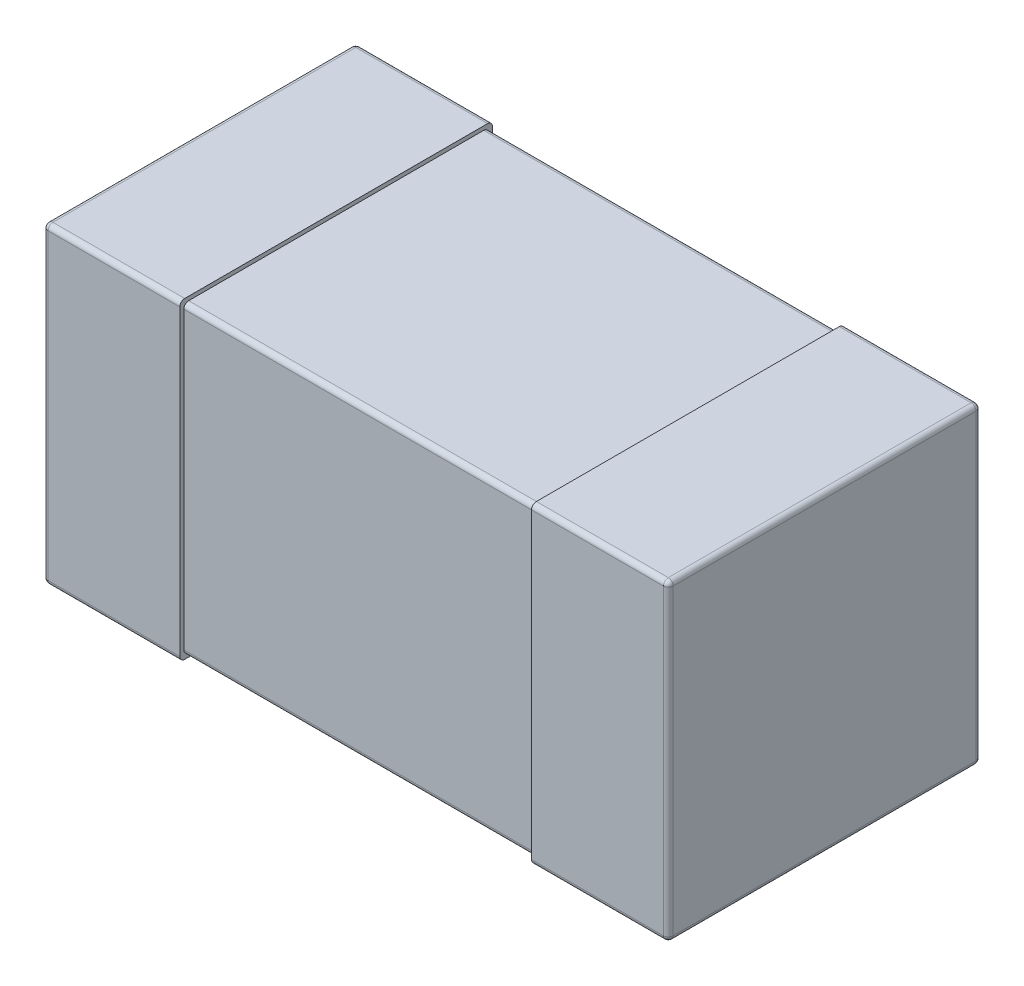
SolidWorks part; units mm, degrees
ref_plane "Спереди" through (0, 0, 0) normal (0, 0, 1) x (1, 0, 0)
ref_plane "Сверху" through (0, 0, 0) normal (0, 1, 0) x (1, 0, 0)
ref_plane "Справа" through (0, 0, 0) normal (1, 0, 0) x (0, 0, -1)
sketch "Эскиз3" plane through (0, 0, 0) normal (0, 0, 1) x (1, 0, 0)
  line L0 (0, 0.7005) -> (0, -0.7992) construction
  line L1 (1.6, 0.8) -> (1.6, -0.8)
  line L2 (1.6, 0.8) -> (0.9, 0.8)
  line L3 (0.9, 0.8) -> (0.9, -0.8)
  line L4 (1.6, -0.8) -> (0.9, -0.8)
  line L5 (-1.6, 0.8) -> (-0.9, 0.8)
  line L6 (-1.6, 0.8) -> (-1.6, -0.8)
  line L7 (-1.6, -0.8) -> (-0.9, -0.8)
  line L8 (-0.9, 0.8) -> (-0.9, -0.8)
  line L9 (-1.6, -0.8) -> (-0.9, 0.8) construction
  line L10 (-1.6, 0.8) -> (-0.9, -0.8) construction
  line L11 (0, 0) -> (-1.25, 0) construction
  point P11 (-1.25, 0)
  dimension "D1" = 0.7
  dimension "D2" = 1.6
  dimension "D3" = 3.2
extrude "Вытянуть3" add sketch "Эскиз3" along normal blind 1.6
sketch "Эскиз4" plane through (0, 0, 0) normal (0, 0, 1) x (1, 0, 0)
  line L1 (0.9, -0.78) -> (-0.9, -0.78)
  line L2 (0.9, -0.78) -> (0.9, 0.78)
  line L3 (0.9, 0.78) -> (-0.9, 0.78)
  line L4 (-0.9, -0.78) -> (-0.9, 0.78)
  line L5 (0.9, -0.78) -> (-0.9, 0.78) construction
  line L6 (0.9, 0.78) -> (-0.9, -0.78) construction
  line L7 (-0.9, -0.8) -> (-0.9, 0.8) construction
  point P0 (0, 0)
  dimension "D1" = 0.02
extrude "Бобышка-Вытянуть3" add sketch "Эскиз4" along normal offset from surface (1.56 mm away) 0.02 from offset 0.02 up to face at (-1.25, 0, 1.6)
fillet "Скругление2" radius 0.025 16 edges at (-1.6, 0.8, 0.8) (-1.6, 0, 1.6) (-1.6, -0.8, 0.8) (-1.6, 0, 0) (-1.25, 0.8, 0) (-1.25, -0.8, 0) (-1.25, 0.8, 1.6) (-1.25, -0.8, 1.6) (1.6, -0.8, 0.8) (1.6, 0, 1.6) (1.6, 0.8, 0.8) (1.6, 0, 0) (1.25, 0.8, 0) (1.25, 0.8, 1.6) (1.25, -0.8, 1.6) (1.25, -0.8, 0)
fillet "Скругление3" radius 0.025 4 edges at (0, -0.78, 0.02) (0, 0.78, 0.02) (0, 0.78, 1.58) (0, -0.78, 1.58)
